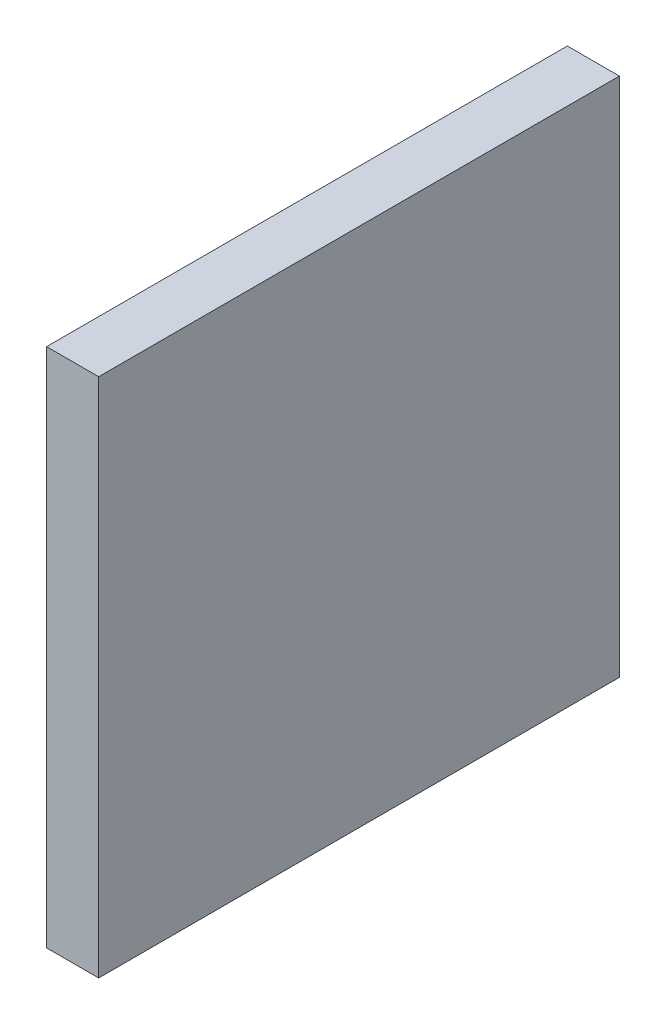
SolidWorks part; units mm, degrees
ref_plane "Front Plane" through (0, 0, 0) normal (0, 0, 1) x (1, 0, 0)
ref_plane "Top Plane" through (0, 0, 0) normal (0, 1, 0) x (1, 0, 0)
ref_plane "Right Plane" through (0, 0, 0) normal (1, 0, 0) x (0, 0, -1)
sketch "Sketch1" plane through (0, 0, 0) normal (1, 0, 0) x (0, 0, -1)
  line L1 (-50, 50) -> (50, 50)
  line L2 (-50, 50) -> (-50, -50)
  line L3 (-50, -50) -> (50, -50)
  line L4 (50, 50) -> (50, -50)
  line L5 (-50, 50) -> (50, -50) construction
  line L6 (-50, -50) -> (50, 50) construction
  point P0 (0, 0)
  dimension "D1" = 100
  dimension "D2" = 100
extrude "Boss-Extrude1" add sketch "Sketch1" along normal blind 10
